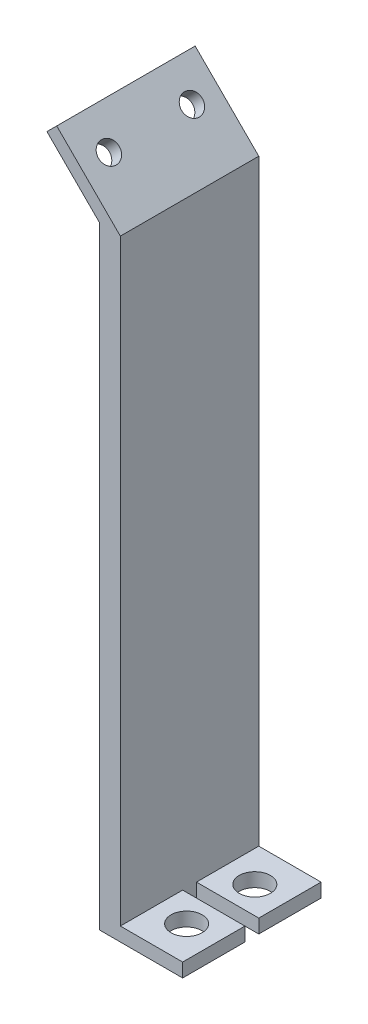
SolidWorks part; units mm, degrees
ref_plane "前视基准面" through (0, 0, 0) normal (0, 0, 1) x (1, 0, 0)
ref_plane "上视基准面" through (0, 0, 0) normal (0, 1, 0) x (1, 0, 0)
ref_plane "右视基准面" through (0, 0, 0) normal (1, 0, 0) x (0, 0, -1)
other "Configuration Table"
ref_plane "基准面1" through (0, 0, 14.375) normal (0, 0, 1) x (1, 0, 0)
sketch "草图1" plane through (0, 0, 14.375) normal (0, 0, 1) x (1, 0, 0)
  line L0 (8.875, -83.5) -> (11.875, -83.5)
  line L1 (11.875, -83.5) -> (11.875, 4.8284)
  line L2 (11.875, 4.8284) -> (2.6826, 14.0208)
  line L3 (2.6826, 14.0208) -> (1.2684, 12.6066)
  line L4 (1.2684, 12.6066) -> (8.875, 5)
  line L5 (8.875, 5) -> (8.875, -83.5)
extrude "凸台-拉伸1" add sketch "草图1" against normal blind 20
sketch "草图2" plane through (11.875, 0, 0) normal (1, 0, 0) x (0, 0, -1)
  line L0 (-5.375, -83.5) -> (-14.375, -83.5)
  line L1 (-14.375, -83.5) -> (-14.375, -81.5)
  line L2 (-14.375, -81.5) -> (-5.375, -81.5)
  line L3 (-5.375, -81.5) -> (-5.375, -83.5)
extrude "凸台-拉伸2" add sketch "草图2" along normal blind 9
sketch "草图3" plane through (11.875, 0, 0) normal (1, 0, 0) x (0, 0, -1)
  line L0 (-3.375, -81.5) -> (5.625, -81.5)
  line L1 (5.625, -81.5) -> (5.625, -83.5)
  line L2 (5.625, -83.5) -> (-3.375, -83.5)
  line L3 (-3.375, -83.5) -> (-3.375, -81.5)
extrude "凸台-拉伸3" add sketch "草图3" along normal blind 9
hole_wizard "Ø3.0 (3) 直径孔1" positions "草图5" profile "草图4" hole size "Ø3.0" standard "ANSI Metric"
sketch "草图5" plane through (6.9375, 6.9375, 0) normal (-0.7071, -0.7071, 0) x (0, 0, 1)
  point P0 (10.375, 3.0173)
  point P1 (-1.625, 3.0173)
sketch "草图4" plane through (4.8039, 9.0711, 10.375) normal (0, 0, 1) x (0.7071, -0.7071, 0)
  line L0 (0, 0) -> (0, 14.864)
  line L1 (0, 14.864) -> (1.5, 14.864)
  line L2 (1.5, 14.864) -> (1.5, 0)
  line L5 (1.5, 0) -> (0, 0)
  line L11 (0, -6.35) -> (0, 107.95) construction
  dimension "通孔孔直径" = 3
  dimension "通孔孔深度" = 14.864
hole_wizard "Ø4.5 (4.5) 直径孔1" positions "草图7" profile "草图6" hole size "Ø4.5" standard "ANSI Metric"
sketch "草图7" plane through (0, -83.5, 0) normal (0, -1, 0) x (-1, 0, 0)
  point P0 (-16.375, -9.3)
  point P1 (-16.375, 0.55)
sketch "草图6" plane through (16.375, -83.5, 9.3) normal (1, 0, 0) x (0, 0, -1)
  line L0 (0, 0) -> (0, 97.5208)
  line L1 (0, 97.5208) -> (2.25, 97.5208)
  line L2 (2.25, 97.5208) -> (2.25, 0)
  line L5 (2.25, 0) -> (0, 0)
  line L11 (0, -6.35) -> (0, 107.95) construction
  dimension "通孔孔直径" = 4.5
  dimension "通孔孔深度" = 97.5208
